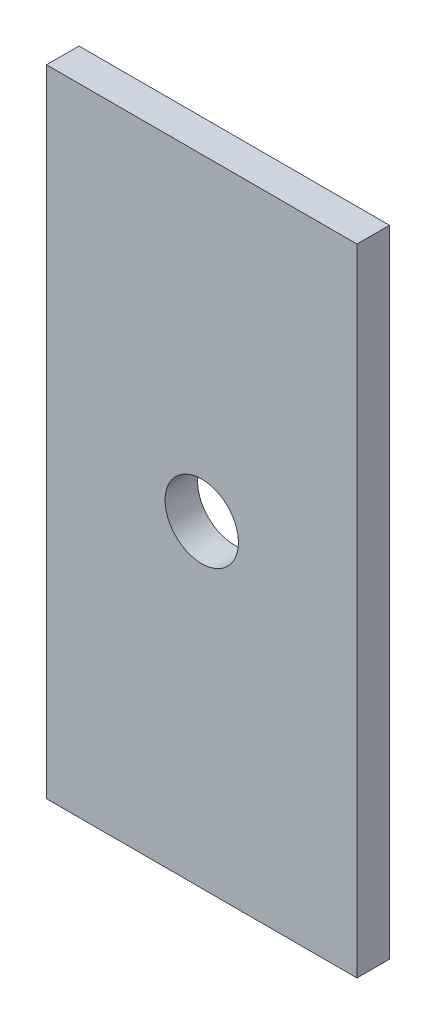
SolidWorks part; units mm, degrees
ref_plane "Front Plane" through (0, 0, 0) normal (0, 0, 1) x (1, 0, 0)
ref_plane "Top Plane" through (0, 0, 0) normal (0, 1, 0) x (1, 0, 0)
ref_plane "Right Plane" through (0, 0, 0) normal (1, 0, 0) x (0, 0, -1)
sketch "Sketch1" plane through (0, 0, 0) normal (0, 0, 1) x (1, 0, 0)
  line L1 (0, 0) -> (25.4, 0)
  line L2 (0, 0) -> (0, 52)
  line L3 (0, 52) -> (25.4, 52)
  line L4 (25.4, 0) -> (25.4, 52)
  dimension "D1" = 25.4
  dimension "D2" = 52
extrude "Boss-Extrude1" add sketch "Sketch1" along normal blind 2.66
sketch "Sketch2" plane through (0, 0, 0) normal (0, 0, -1) x (-1, 0, 0)
  circle A0 centre (-12.7, 26) radius 3
  dimension "D1" = 6
extrude "Cut-Extrude1" cut sketch "Sketch2" against normal blind 10
